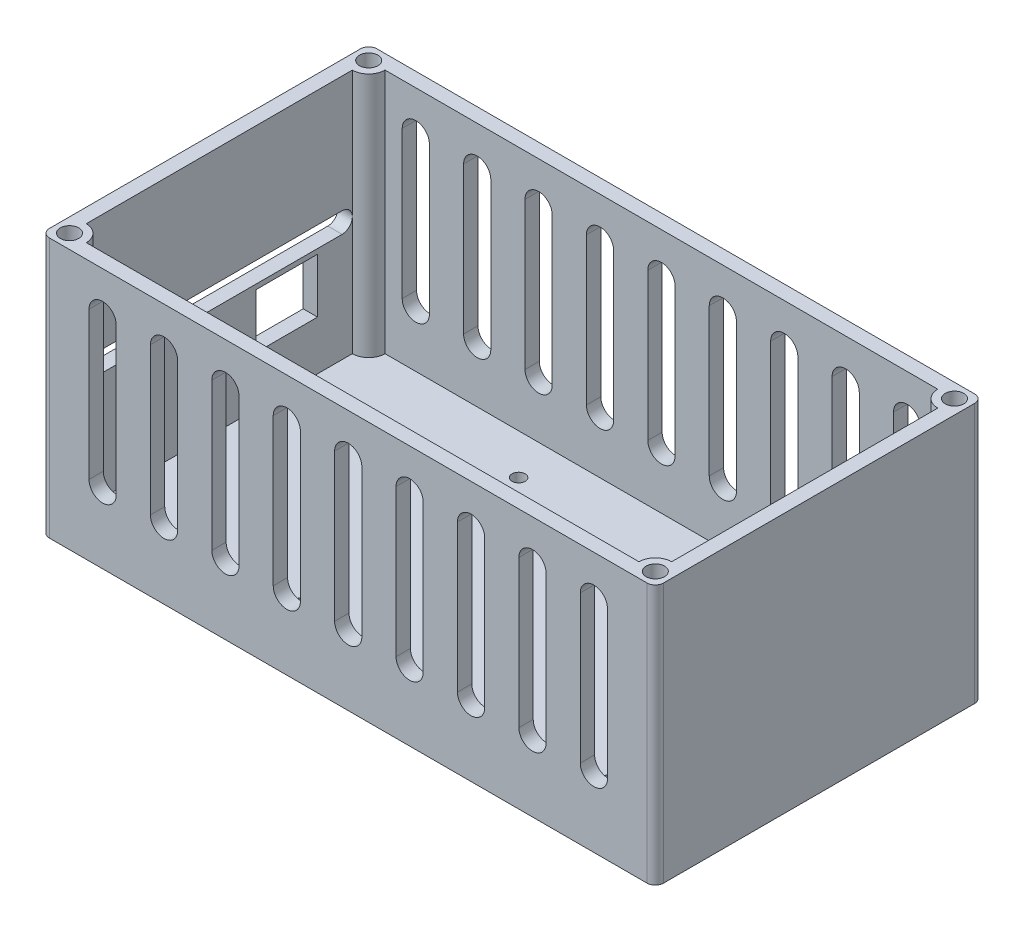
SolidWorks part; units mm, degrees
ref_plane "Front Plane" through (0, 0, 0) normal (0, 0, 1) x (1, 0, 0)
ref_plane "Top Plane" through (0, 0, 0) normal (0, 1, 0) x (1, 0, 0)
ref_plane "Right Plane" through (0, 0, 0) normal (1, 0, 0) x (0, 0, -1)
sketch "Sketch1" plane through (0, 0, 0) normal (0, 1, 0) x (1, 0, 0)
  line L0 (-75, 0) -> (75, 0) construction
  line L1 (-73, -40) -> (73, -40)
  line L2 (-75, -38) -> (-75, 38)
  line L3 (-73, 40) -> (73, 40)
  line L4 (75, -38) -> (75, 38)
  line L5 (-75, -40) -> (75, 40) construction
  line L6 (-75, 40) -> (75, -40) construction
  line L7 (-25, -26.605) -> (-25, 26.605)
  line L8 (49.93, -26.605) -> (49.93, 26.605)
  line L10 (0, 40) -> (0, -40) construction
  circle A0 centre (-25, 26.605) radius 1.6
  circle A1 centre (49.93, 26.605) radius 1.6
  circle A2 centre (49.93, -26.605) radius 1.6
  circle A3 centre (-25, -26.605) radius 1.6
  arc A4 (73, 40) -> (75, 38) centre (73, 38) cw
  arc A5 (75, -38) -> (73, -40) centre (73, -38) cw
  arc A6 (-73, -40) -> (-75, -38) centre (-73, -38) cw
  arc A7 (-75, 38) -> (-73, 40) centre (-73, 38) cw
  circle A8 centre (-45, 0) radius 1.6
  circle A9 centre (35, 0) radius 1.6
  point P0 (0, 0)
  point P11 (-25, 0)
  point P14 (49.93, 0)
  point P33 (-71.5, 0)
  point P38 (0, 36.5)
  dimension "D8" = 3.2
  dimension "D9" = 3.2
  dimension "D10" = 3.2
  dimension "D11" = 3.2
  dimension "D12" = 2
  dimension "D13" = 3.2
  dimension "D14" = 3.2
  dimension "D1" = 150
  dimension "D2" = 80
  dimension "D3" = 90
  dimension "D4" = 53.21
  dimension "D5" = 53.21
  dimension "D6" = 74.93
  dimension "D7" = 50
  dimension "D15" = 30
  dimension "D16" = 80
extrude "Boss-Extrude1" add sketch "Sketch1" along normal blind 3.5
sketch "Sketch2" plane through (0, 3.5, 0) normal (0, 1, 0) x (1, 0, 0)
  line L0 (-71.5, 36.5) -> (-71.5, -36.5)
  line L1 (73, -40) -> (-73, -40)
  line L2 (75, -38) -> (75, 38)
  line L3 (73, 40) -> (-73, 40)
  line L4 (-75, -38) -> (-75, 38)
  line L5 (75, -40) -> (-75, 40) construction
  line L6 (75, 40) -> (-75, -40) construction
  line L7 (71.5, 36.5) -> (-71.5, 36.5)
  line L8 (-71.5, -36.5) -> (71.5, -36.5)
  line L9 (71.5, -36.5) -> (71.5, 36.5)
  line L10 (-71.5, 0) -> (71.5, 0) construction
  line L11 (0, 36.5) -> (0, -36.5) construction
  arc A0 (73, 40) -> (75, 38) centre (73, 38) cw
  arc A1 (75, -38) -> (73, -40) centre (73, -38) cw
  arc A2 (-73, -40) -> (-75, -38) centre (-73, -38) cw
  arc A3 (-75, 38) -> (-73, 40) centre (-73, 38) cw
  arc A4 (-67.5, 36.5) -> (-71.5, 32.5) centre (-71.5, 36.5) cw
  arc A5 (67.5, 36.5) -> (71.5, 32.5) centre (71.5, 36.5) ccw
  arc A6 (-67.5, -36.5) -> (-71.5, -32.5) centre (-71.5, -36.5) ccw
  arc A7 (67.5, -36.5) -> (71.5, -32.5) centre (71.5, -36.5) cw
  point P0 (0, 0)
  point P22 (0, 36.5)
  point P25 (0, 0)
  arc M19 (-73, 40) -> (-75, 38) centre (-73, 38) ccw
  line M20 (-75, 38) -> (-75, -38)
  arc M21 (-75, -38) -> (-73, -40) centre (-73, -38) ccw
  line M22 (-73, -40) -> (73, -40)
  arc M23 (73, -40) -> (75, -38) centre (73, -38) ccw
  line M24 (75, -38) -> (75, 38)
  arc M25 (75, 38) -> (73, 40) centre (73, 38) ccw
  line M26 (73, 40) -> (-73, 40)
  dimension "D1" = 2
  dimension "D2" = 4
extrude "Boss-Extrude2" add sketch "Sketch2" along normal blind 60 contours L9 L8 L0 L7 M26 M19 M20 M21 M22 M23 M24 M25 | A4 L7 L0 | L8 A6 L0 | L7 A5 L9 | A7 L8 L9
sketch "Sketch3" plane through (0, 0, 40) normal (0, 0, 1) x (1, 0, 0)
  line L0 (-73, 31.75) -> (73, 31.75) construction
  line L1 (-73, 63.5) -> (-73, 0) construction
  line L2 (73, 63.5) -> (73, 0) construction
  line L3 (0, 63.5) -> (0, 0) construction
  line L4 (-73, 63.5) -> (73, 63.5) construction
  line L5 (-73, 0) -> (73, 0) construction
  line L6 (0, 17.25) -> (0, 53.25) construction
  line L7 (-3.3208, 17.25) -> (-3.3208, 53.25)
  line L8 (3.3208, 17.25) -> (3.3208, 53.25)
  line L9 (18.3208, 17.25) -> (18.3208, 53.25)
  line L10 (11.6792, 17.25) -> (11.6792, 53.25)
  line L11 (15, 17.25) -> (15, 53.25) construction
  line L12 (33.3208, 17.25) -> (33.3208, 53.25)
  line L13 (26.6792, 17.25) -> (26.6792, 53.25)
  line L14 (30, 17.25) -> (30, 53.25) construction
  line L15 (48.3208, 17.25) -> (48.3208, 53.25)
  line L16 (41.6792, 17.25) -> (41.6792, 53.25)
  line L17 (45, 17.25) -> (45, 53.25) construction
  line L18 (63.3208, 17.25) -> (63.3208, 53.25)
  line L19 (56.6792, 17.25) -> (56.6792, 53.25)
  line L20 (60, 17.25) -> (60, 53.25) construction
  line L21 (3.3208, 17.25) -> (3.3208, 53.25)
  line L22 (-3.3208, 17.25) -> (-3.3208, 53.25)
  line L23 (0, 17.25) -> (0, 53.25) construction
  line L24 (18.3208, 17.25) -> (18.3208, 53.25)
  line L25 (11.6792, 17.25) -> (11.6792, 53.25)
  line L26 (15, 17.25) -> (15, 53.25) construction
  line L27 (33.3208, 17.25) -> (33.3208, 53.25)
  line L28 (26.6792, 17.25) -> (26.6792, 53.25)
  line L29 (30, 17.25) -> (30, 53.25) construction
  line L30 (48.3208, 17.25) -> (48.3208, 53.25)
  line L31 (41.6792, 17.25) -> (41.6792, 53.25)
  line L32 (45, 17.25) -> (45, 53.25) construction
  line L33 (-11.6792, 17.25) -> (-11.6792, 53.25)
  line L34 (-18.3208, 17.25) -> (-18.3208, 53.25)
  line L35 (-15, 17.25) -> (-15, 53.25) construction
  line L36 (3.3208, 17.25) -> (3.3208, 53.25)
  line L37 (-3.3208, 17.25) -> (-3.3208, 53.25)
  line L38 (0, 17.25) -> (0, 53.25) construction
  line L39 (18.3208, 17.25) -> (18.3208, 53.25)
  line L40 (11.6792, 17.25) -> (11.6792, 53.25)
  line L41 (15, 17.25) -> (15, 53.25) construction
  line L42 (33.3208, 17.25) -> (33.3208, 53.25)
  line L43 (26.6792, 17.25) -> (26.6792, 53.25)
  line L44 (30, 17.25) -> (30, 53.25) construction
  line L45 (-26.6792, 17.25) -> (-26.6792, 53.25)
  line L46 (-33.3208, 17.25) -> (-33.3208, 53.25)
  line L47 (-30, 17.25) -> (-30, 53.25) construction
  line L48 (-11.6792, 17.25) -> (-11.6792, 53.25)
  line L49 (-18.3208, 17.25) -> (-18.3208, 53.25)
  line L50 (-15, 17.25) -> (-15, 53.25) construction
  line L51 (3.3208, 17.25) -> (3.3208, 53.25)
  line L52 (-3.3208, 17.25) -> (-3.3208, 53.25)
  line L53 (0, 17.25) -> (0, 53.25) construction
  line L54 (18.3208, 17.25) -> (18.3208, 53.25)
  line L55 (11.6792, 17.25) -> (11.6792, 53.25)
  line L56 (15, 17.25) -> (15, 53.25) construction
  line L57 (-41.6792, 17.25) -> (-41.6792, 53.25)
  line L58 (-48.3208, 17.25) -> (-48.3208, 53.25)
  line L59 (-45, 17.25) -> (-45, 53.25) construction
  line L60 (-26.6792, 17.25) -> (-26.6792, 53.25)
  line L61 (-33.3208, 17.25) -> (-33.3208, 53.25)
  line L62 (-30, 17.25) -> (-30, 53.25) construction
  line L63 (-11.6792, 17.25) -> (-11.6792, 53.25)
  line L64 (-18.3208, 17.25) -> (-18.3208, 53.25)
  line L65 (-15, 17.25) -> (-15, 53.25) construction
  line L66 (3.3208, 17.25) -> (3.3208, 53.25)
  line L67 (-3.3208, 17.25) -> (-3.3208, 53.25)
  line L68 (0, 17.25) -> (0, 53.25) construction
  line L69 (-11.6792, 17.25) -> (-11.6792, 53.25)
  line L70 (-18.3208, 17.25) -> (-18.3208, 53.25)
  line L71 (-15, 17.25) -> (-15, 53.25) construction
  line L72 (-26.6792, 17.25) -> (-26.6792, 53.25)
  line L73 (-33.3208, 17.25) -> (-33.3208, 53.25)
  line L74 (-30, 17.25) -> (-30, 53.25) construction
  line L75 (-41.6792, 17.25) -> (-41.6792, 53.25)
  line L76 (-48.3208, 17.25) -> (-48.3208, 53.25)
  line L77 (-45, 17.25) -> (-45, 53.25) construction
  line L78 (-56.6792, 17.25) -> (-56.6792, 53.25)
  line L79 (-63.3208, 17.25) -> (-63.3208, 53.25)
  line L80 (-60, 17.25) -> (-60, 53.25) construction
  arc A0 (-3.3208, 17.25) -> (3.3208, 17.25) centre (0, 17.25) ccw
  arc A1 (3.3208, 53.25) -> (-3.3208, 53.25) centre (0, 53.25) ccw
  arc A2 (11.6792, 17.25) -> (18.3208, 17.25) centre (15, 17.25) ccw
  arc A3 (18.3208, 53.25) -> (11.6792, 53.25) centre (15, 53.25) ccw
  arc A4 (26.6792, 17.25) -> (33.3208, 17.25) centre (30, 17.25) ccw
  arc A5 (33.3208, 53.25) -> (26.6792, 53.25) centre (30, 53.25) ccw
  arc A6 (41.6792, 17.25) -> (48.3208, 17.25) centre (45, 17.25) ccw
  arc A7 (48.3208, 53.25) -> (41.6792, 53.25) centre (45, 53.25) ccw
  arc A8 (56.6792, 17.25) -> (63.3208, 17.25) centre (60, 17.25) ccw
  arc A9 (63.3208, 53.25) -> (56.6792, 53.25) centre (60, 53.25) ccw
  arc A10 (-3.3208, 17.25) -> (3.3208, 17.25) centre (0, 17.25) ccw
  arc A11 (3.3208, 53.25) -> (-3.3208, 53.25) centre (0, 53.25) ccw
  arc A12 (11.6792, 17.25) -> (18.3208, 17.25) centre (15, 17.25) ccw
  arc A13 (18.3208, 53.25) -> (11.6792, 53.25) centre (15, 53.25) ccw
  arc A14 (26.6792, 17.25) -> (33.3208, 17.25) centre (30, 17.25) ccw
  arc A15 (33.3208, 53.25) -> (26.6792, 53.25) centre (30, 53.25) ccw
  arc A16 (41.6792, 17.25) -> (48.3208, 17.25) centre (45, 17.25) ccw
  arc A17 (48.3208, 53.25) -> (41.6792, 53.25) centre (45, 53.25) ccw
  arc A18 (-18.3208, 17.25) -> (-11.6792, 17.25) centre (-15, 17.25) ccw
  arc A19 (-11.6792, 53.25) -> (-18.3208, 53.25) centre (-15, 53.25) ccw
  arc A20 (-3.3208, 17.25) -> (3.3208, 17.25) centre (0, 17.25) ccw
  arc A21 (3.3208, 53.25) -> (-3.3208, 53.25) centre (0, 53.25) ccw
  arc A22 (11.6792, 17.25) -> (18.3208, 17.25) centre (15, 17.25) ccw
  arc A23 (18.3208, 53.25) -> (11.6792, 53.25) centre (15, 53.25) ccw
  arc A24 (26.6792, 17.25) -> (33.3208, 17.25) centre (30, 17.25) ccw
  arc A25 (33.3208, 53.25) -> (26.6792, 53.25) centre (30, 53.25) ccw
  arc A26 (-33.3208, 17.25) -> (-26.6792, 17.25) centre (-30, 17.25) ccw
  arc A27 (-26.6792, 53.25) -> (-33.3208, 53.25) centre (-30, 53.25) ccw
  arc A28 (-18.3208, 17.25) -> (-11.6792, 17.25) centre (-15, 17.25) ccw
  arc A29 (-11.6792, 53.25) -> (-18.3208, 53.25) centre (-15, 53.25) ccw
  arc A30 (-3.3208, 17.25) -> (3.3208, 17.25) centre (0, 17.25) ccw
  arc A31 (3.3208, 53.25) -> (-3.3208, 53.25) centre (0, 53.25) ccw
  arc A32 (11.6792, 17.25) -> (18.3208, 17.25) centre (15, 17.25) ccw
  arc A33 (18.3208, 53.25) -> (11.6792, 53.25) centre (15, 53.25) ccw
  arc A34 (-48.3208, 17.25) -> (-41.6792, 17.25) centre (-45, 17.25) ccw
  arc A35 (-41.6792, 53.25) -> (-48.3208, 53.25) centre (-45, 53.25) ccw
  arc A36 (-33.3208, 17.25) -> (-26.6792, 17.25) centre (-30, 17.25) ccw
  arc A37 (-26.6792, 53.25) -> (-33.3208, 53.25) centre (-30, 53.25) ccw
  arc A38 (-18.3208, 17.25) -> (-11.6792, 17.25) centre (-15, 17.25) ccw
  arc A39 (-11.6792, 53.25) -> (-18.3208, 53.25) centre (-15, 53.25) ccw
  arc A40 (-3.3208, 17.25) -> (3.3208, 17.25) centre (0, 17.25) ccw
  arc A41 (3.3208, 53.25) -> (-3.3208, 53.25) centre (0, 53.25) ccw
  arc A42 (-18.3208, 17.25) -> (-11.6792, 17.25) centre (-15, 17.25) ccw
  arc A43 (-11.6792, 53.25) -> (-18.3208, 53.25) centre (-15, 53.25) ccw
  arc A44 (-33.3208, 17.25) -> (-26.6792, 17.25) centre (-30, 17.25) ccw
  arc A45 (-26.6792, 53.25) -> (-33.3208, 53.25) centre (-30, 53.25) ccw
  arc A46 (-48.3208, 17.25) -> (-41.6792, 17.25) centre (-45, 17.25) ccw
  arc A47 (-41.6792, 53.25) -> (-48.3208, 53.25) centre (-45, 53.25) ccw
  arc A48 (-63.3208, 17.25) -> (-56.6792, 17.25) centre (-60, 17.25) ccw
  arc A49 (-56.6792, 53.25) -> (-63.3208, 53.25) centre (-60, 53.25) ccw
  point P14 (0, 35.25)
  point P24 (15, 35.25)
  point P31 (30, 35.25)
  point P38 (45, 35.25)
  point P45 (60, 35.25)
  point P52 (0, 35.25)
  point P59 (15, 35.25)
  point P66 (30, 35.25)
  point P73 (45, 35.25)
  point P80 (-15, 35.25)
  point P87 (0, 35.25)
  point P94 (15, 35.25)
  point P101 (30, 35.25)
  point P108 (-30, 35.25)
  point P115 (-15, 35.25)
  point P122 (0, 35.25)
  point P129 (15, 35.25)
  point P136 (-45, 35.25)
  point P143 (-30, 35.25)
  point P150 (-15, 35.25)
  point P157 (0, 35.25)
  point P164 (-15, 35.25)
  point P171 (-30, 35.25)
  point P178 (-45, 35.25)
  point P185 (-60, 35.25)
  dimension "D1" = 3.5
  dimension "D2" = 18
  dimension "D5" = 3.3208
  dimension "D3" = 5
  dimension "D4" = 5
extrude "Cut-Extrude1" cut sketch "Sketch3" against normal through all contours L18 A9 L19 A8 | L15 A7 L16 A6 | L12 A5 L13 A4 | L9 A3 L10 A2 | L8 A1 L7 A0 | L33 A19 L34 A18 | L45 A27 L46 A26 | L57 A35 L58 A34 | L78 A49 L79 A48
sketch "Sketch5" plane through (-75, 0, 0) normal (-1, 0, 0) x (0, 0, 1)
  line L0 (38, 63.5) -> (38, 0) construction
  line L1 (-38, 63.5) -> (38, 63.5)
  line L2 (-38, 63.5) -> (-38, 3.5)
  line L3 (-38, 3.5) -> (38, 3.5)
  line L4 (38, 63.5) -> (38, 3.5)
  line L5 (38, 0) -> (-38, 0) construction
  line L6 (-38, 15.5) -> (38, 15.5) construction
  line L7 (0, 0) -> (0, 63.5) construction
  line L8 (-24, 15.5) -> (-9, 15.5)
  line L9 (-24, 15.5) -> (-24, 28.8063)
  line L10 (-24, 28.8063) -> (-9, 28.8063)
  line L11 (-9, 15.5) -> (-9, 28.8063)
  line L12 (30, 32.5) -> (-30, 32.5) construction
  line L13 (30, 30) -> (-30, 30)
  line L14 (30, 35) -> (-30, 35)
  arc A0 (30, 30) -> (30, 35) centre (30, 32.5) ccw
  arc A1 (-30, 35) -> (-30, 30) centre (-30, 32.5) ccw
  point P20 (0, 32.5)
  dimension "D1" = 3.5
  dimension "D2" = 12
  dimension "D3" = 14
  dimension "D4" = 15
  dimension "D5" = 5
  dimension "D6" = 30
  dimension "D7" = 30
extrude "Cut-Extrude2" cut sketch "Sketch5" against normal up to next contours L8 L11 L10 L9 | L14 A1 L13 A0
sketch "Sketch6" plane through (0, 63.5, 0) normal (0, 1, 0) x (1, 0, 0)
  line L0 (-74.4142, 39.4142) -> (-68.6716, 33.6716) construction
  line L1 (0, 40) -> (0, -40) construction
  line L2 (73, 40) -> (-73, 40) construction
  line L3 (-73, -40) -> (73, -40) construction
  line L4 (-75, 0) -> (75, 0) construction
  line L5 (-75, 38) -> (-75, -38) construction
  line L6 (75, -38) -> (75, 38) construction
  arc A0 (-73, 40) -> (-75, 38) centre (-73, 38) ccw construction
  arc A1 (-71.5, 32.5) -> (-67.5, 36.5) centre (-71.5, 36.5) ccw construction
  circle A2 centre (-71.5429, 36.5429) radius 2.25
  circle A3 centre (71.5429, 36.5429) radius 2.25
  circle A4 centre (71.5429, -36.5429) radius 2.25
  circle A5 centre (-71.5429, -36.5429) radius 2.25
  point P22 (0, 0)
  dimension "D1" = 4.5
extrude "Cut-Extrude3" cut sketch "Sketch6" against normal blind 20
